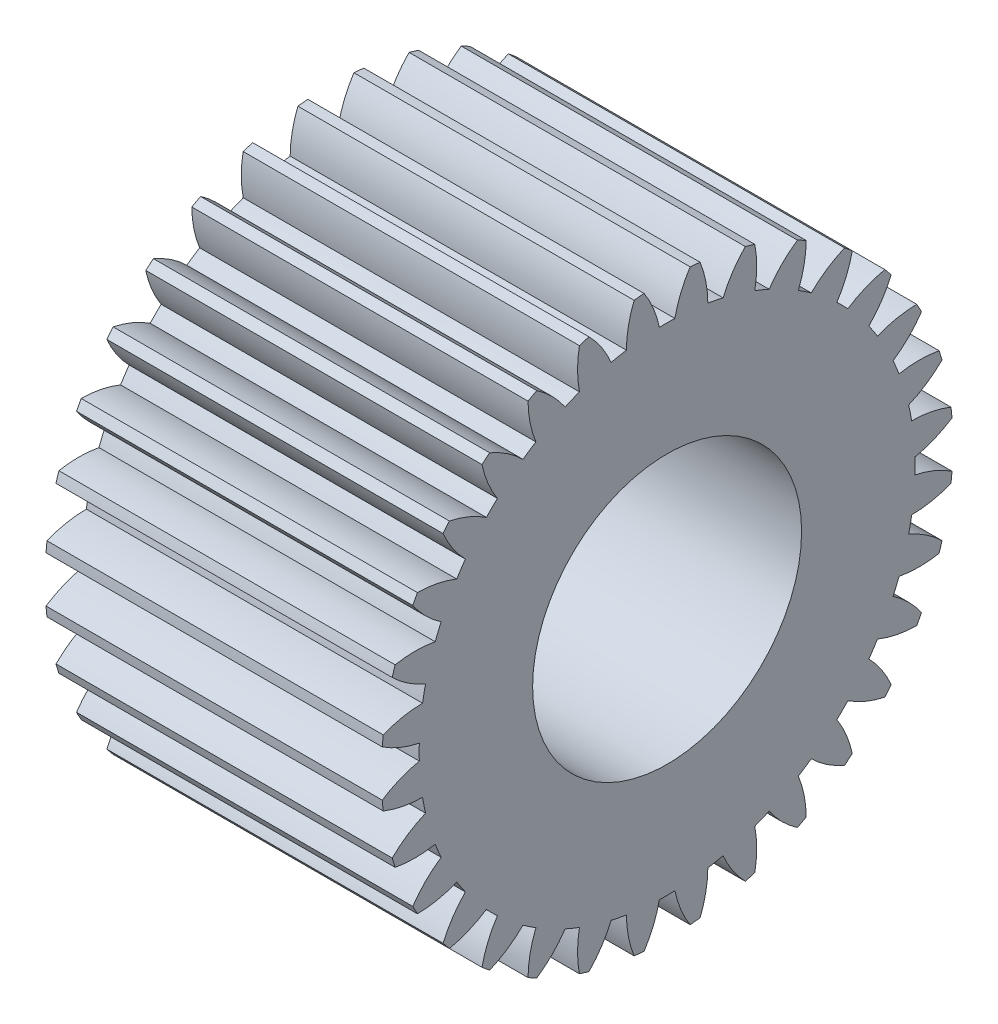
SolidWorks part; units mm, degrees
ref_plane "Plane1" through (0, 0, 0) normal (0, 0, 1) x (1, 0, 0)
ref_plane "Plane2" through (0, 0, 0) normal (0, 1, 0) x (1, 0, 0)
ref_plane "Plane3" through (0, 0, 0) normal (1, 0, 0) x (0, 0, -1)
sketch "HoldingSke" plane through (0, 0, 0) normal (0, 1, 0) x (1, 0, 0)
  line L0 (0, 0) -> (1.6961, -1.0598)
  line L1 (-15, 0) -> (100, 0) construction
  line L2 (0, 0) -> (-2.1039, 2.3779)
  line L3 (0, 0) -> (-11.863, 4.5341)
  line L4 (0, 0) -> (7.3237, 4.5764)
  line L5 (0, 0) -> (-46.8476, -17.4728)
  line L6 (0, 0) -> (-8.2896, -5.593)
  line L7 (-2.1039, 2.3779) -> (8.6586, 51.2059)
  line L8 (-76.2, 54.61) -> (-74.8, 54.61)
  line L9 (-71.009, 38.7566) -> (-53.1078, 45.2721)
  line L10 (-76.2, 71.12) -> (104.1128, 71.12)
  line L11 (0, 0) -> (-10, 0)
  line L12 (-76.2, 101.6) -> (-76.181, 101.6)
  line L13 (24.9733, 27.94) -> (52.9518, 28.4284)
  line L14 (24.9733, 27.94) -> (24.9743, 27.94)
  line L15 (24.9733, 27.94) -> (100.4006, 29.5858)
  line L16 (-63.627, -0.5) -> (-12.827, -0.5)
  circle A0 centre (0, 0) radius 4
  circle A1 centre (0, 0) radius 7.374
  circle A2 centre (0, 0) radius 37.5
  circle A3 centre (0, 0) radius 4
  dimension "MHD" = 14.748
  dimension "Hub_dia" = 75
  dimension "Bore" = 8
  dimension "MBD" = 8
  dimension "Num_teeth" = 32
  dimension "Pitch" = 2
  dimension "Overall_len" = 50
  dimension "Show_teeth" = 32
  dimension "Thickness" = 10
  dimension "OAL" = 50.0001
  dimension "T_dim" = 1.4
  dimension "Ap" = 20
  dimension "H" = 19.05
  dimension "Pitch_radius" = 180.3128
  dimension "Width" = 10
  dimension "Backlash" = 0.019
  dimension "Addendum_fac" = 1
  dimension "Dedendum_fac" = 1.25
  dimension "Clearance_fac" = 0.25
  dimension "Dedendum_add" = 0.001
  dimension "Module" = 0.5
sketch "BasProSke" plane through (0, 0, 0) normal (0, 1, 0) x (1, 0, 0)
  line L0 (-10, 0) -> (60, 0) construction
  line L1 (0, 0) -> (0, 8.5)
  line L2 (0, 0) -> (10, 0)
  line L3 (10, 0) -> (10, 8.5)
  line L4 (10, 8.5) -> (0, 8.5)
  dimension "Thickness" = 10
  dimension "Diameter" = 17
revolve "Base-Revolve" add sketch "BasProSke" angle 360 about L0
sketch "TooCutSke" plane through (0, 0, 0) normal (1, 0, 0) x (0, 0, -1)
  line L1 (0, 0) -> (0, 107) construction
  line L2 (0, 0) -> (-0.4258, 7.9887) construction
  line L3 (0, 0) -> (-1.5667, 15.9069) construction
  line L4 (-0.4258, 7.9887) -> (-0.7833, 7.9534) construction
  arc A0 (0.2309, 7.3704) -> (-0.2309, 7.3704) centre (0, 0) ccw
  arc A1 (0.7014, 8.4965) -> (-0.7014, 8.4965) centre (0, 0) ccw
  circle A2 centre (0, 0) radius 8 construction
  circle A3 centre (0, 0) radius 7.5175 construction
  arc A4 (-0.2309, 7.3704) -> (-0.7014, 8.4965) centre (-3.3647, 6.7225) ccw
  arc A5 (0.7014, 8.4965) -> (0.2309, 7.3704) centre (3.3647, 6.7225) ccw
  dimension "Root_dia" = 14.748
  dimension "Overcut_dia" = 17.0508
  dimension "Pitch_dia" = 16
  dimension "Base_dia" = 15.0351
  dimension "Flank_rad" = 3.2
  dimension "Half_ang" = 5.625
  dimension "Half_CT" = 0.3593
extrude "ToothCut" cut sketch "TooCutSke" along normal through all
fillet "Breaks" [suppressed] radius 0.01
fillet "RootFillets" [suppressed] radius 0.126
pattern_circular "TeethCuts" count 32 every 11.25 about axis through (-10, 0, 0) along (1, 0, 0) of "ToothCut", "RootFillets", "Breaks"
sketch "HubNeaOneSke" plane through (0, 0, 0) normal (-1, 0, 0) x (0, 0, 1)
  circle A0 centre (0, 0) radius 7.374
  dimension "Diameter" = 14.748
extrude "HubNearOne" [suppressed] add sketch "HubNeaOneSke" along normal blind 40.0001
sketch "HubNeaBotSke" plane through (0, 0, 0) normal (-1, 0, 0) x (0, 0, 1)
  circle A0 centre (0, 0) radius 7.374
  dimension "Diameter" = 14.748
extrude "HubNearBoth" [suppressed] add sketch "HubNeaBotSke" along normal blind 20
ref_plane "FarPln" through (10, 0, 0) normal (1, 0, 0) x (0, 0, -1)
sketch "HubFarSke" plane through (10, 0, 0) normal (1, 0, 0) x (0, 0, -1)
  circle A0 centre (0, 0) radius 7.374
  dimension "Diameter" = 14.748
extrude "HubFar" [suppressed] add sketch "HubFarSke" along normal blind 20
sketch "BorSke" plane through (0, 0, 0) normal (1, 0, 0) x (0, 0, -1)
  circle A0 centre (0, 0) radius 4
  dimension "Diameter" = 8
extrude "Bore" cut sketch "BorSke" along normal mid plane 100.0001
sketch "KeySke" plane through (0, 0, 0) normal (1, 0, 0) x (0, 0, -1)
  line L0 (-1.5, 0) -> (-1.5, 5.4)
  line L1 (-1.5, 5.4) -> (1.5, 5.4)
  line L2 (1.5, 5.4) -> (1.5, 0)
  line L3 (0, 0) -> (0, 34) construction
  line L4 (-1.5, 0) -> (1.5, 0)
  dimension "Offset" = 5.4
  dimension "Width" = 3
extrude "Keyway" [suppressed] cut sketch "KeySke" along normal mid plane 100.0001
pattern_circular "Keyway2" [suppressed] count 2 every 90 about axis through (-10, 0, 0) along (1, 0, 0)
equation "' \"Module@HoldingSke\" = 6.35"
equation "' \"Num_teeth@HoldingSke\" = 12"
equation "' \"Ap@HoldingSke\" =  20"
equation "' \"Ap@HoldingSke\" = 20"
equation "' \"Width@HoldingSke\" = 0.5 * 25.4"
equation "' \"Hub_dia@HoldingSke\"= 1 * 25.4"
equation "' \"Hub_dia@HoldingSke\" = 1 * 25.4"
equation "' \"Overall_len@HoldingSke\" = 1.0 * 25.4"
equation "' \"Bore@HoldingSke\" = 0.75 * 25.4"
equation "' \"T_dim@HoldingSke\" = 0.1 * 25.4"
equation "' \"Width@KeySke\" = 0.25 * 25.4"
equation "' \"Show_teeth@HoldingSke\" = 13"
equation "' \"Backlash@HoldingSke\" = 0.009 * 25.4"
equation "' \"Addendum_fac@HoldingSke\" = 1.0"
equation "' \"Dedendum_fac@HoldingSke\" = 1.25"
equation "' \"Dedendum_add@HoldingSke\" = 0.00005 * 25.4"
equation "' \"Clearance_fac@HoldingSke\" = 0.25"
equation "\"Pitch@HoldingSke\" = 1 / \"Module@HoldingSke\""
equation "\"Overcut_dia@TooCutSke\" = (\"Num_teeth@HoldingSke\" + 2 * \"Addendum_fac@HoldingSke\") / \"Pitch@HoldingSke\" + 0.002 * 25.4"
equation "\"Pitch_dia@TooCutSke\" = \"Num_teeth@HoldingSke\" / \"Pitch@HoldingSke\""
equation "\"Base_dia@TooCutSke\" = \"Num_teeth@HoldingSke\" / \"Pitch@HoldingSke\" * cos((\"Ap@HoldingSke\"  * 3.14159265 / 180))"
equation "\"Root_dia@TooCutSke\" = (\"Num_teeth@HoldingSke\" + 2) / \"Pitch@HoldingSke\" - 2 * (\"Addendum_fac@HoldingSke\" + \"Dedendum_fac@HoldingSke\") / \"Pitch@HoldingSke\" - \"Dedendum_add@HoldingSke\" * 2"
equation "\"Half_ang@TooCutSke\" = 180 / \"Num_teeth@HoldingSke\""
equation "\"Half_CT@TooCutSke\" = \"Num_teeth@HoldingSke\" / \"Pitch@HoldingSke\" * sin((3.14159265 / 2 / \"Num_teeth@HoldingSke\")) / 2 - 7 * \"Backlash@HoldingSke\" / 4"
equation "\"Flank_rad@TooCutSke\" = \"Num_teeth@HoldingSke\" / \"Pitch@HoldingSke\" / 5"
equation "\"Radius@RootFillets\" = \"Clearance_fac@HoldingSke\" / \"Pitch@HoldingSke\" + \"Dedendum_add@HoldingSke\""
equation "\"Break_rad@Breaks\" = 0.02 / \"Pitch@HoldingSke\""
equation "\"Thickness@HoldingSke\" = \"Width@HoldingSke\""
equation "\"OAL@HoldingSke\" = \"Thickness@HoldingSke\""
equation "\"MHD@HoldingSke\" = (\"Num_teeth@HoldingSke\" + 2) / \"Pitch@HoldingSke\" - 2 * (\"Addendum_fac@HoldingSke\" + \"Dedendum_fac@HoldingSke\")  / \"Pitch@HoldingSke\" - \"Dedendum_add@HoldingSke\" * 2"
equation "\"MBD@HoldingSke\" = (\"Num_teeth@HoldingSke\" + 2) / \"Pitch@HoldingSke\" - 2 * (\"Addendum_fac@HoldingSke\" + \"Dedendum_fac@HoldingSke\")  / \"Pitch@HoldingSke\" - \"Dedendum_add@HoldingSke\" * 2 - 0.002 * 25.4"
equation "\"MHD@HoldingSke\" = ((sgn( \"MHD@HoldingSke\" - \"Hub_dia@HoldingSke\" )-1)*( \"MHD@HoldingSke\" - \"Hub_dia@HoldingSke\" ))/-2+ \"Hub_dia@HoldingSke\""
equation "\"MBD@HoldingSke\" = ((sgn( \"MBD@HoldingSke\" - \"Bore@HoldingSke\" )-1)*( \"MBD@HoldingSke\" - \"Bore@HoldingSke\" ))/-2+ \"Bore@HoldingSke\""
equation "\"OAL@HoldingSke\" = ((sgn( \"OAL@HoldingSke\" - \"Overall_len@HoldingSke\" )+1)*( \"OAL@HoldingSke\" - \"Overall_len@HoldingSke\" ))/2 + \"Overall_len@HoldingSke\" + 0.000002 * 25.4"
equation "\"Num_teeth@TeethCuts\" = int( \"Show_teeth@HoldingSke\" ) + 1"
equation "\"Num_teeth@TeethCuts\" = ((sgn( \"Num_teeth@TeethCuts\" - \"Num_teeth@HoldingSke\" )-1)*( \"Num_teeth@TeethCuts\" - \"Num_teeth@HoldingSke\" ))/-2+ \"Num_teeth@HoldingSke\""
equation "\"Num_teeth@TeethCuts\" = ((sgn( \"Num_teeth@TeethCuts\" - 2.0)+1)*( \"Num_teeth@TeethCuts\" - 2.0))/2 +2.0"
equation "\"Angle@TeethCuts\" = 360.0 / \"Num_teeth@HoldingSke\""
equation "\"Diameter@BasProSke\" = (\"Num_teeth@HoldingSke\" + 2 * \"Addendum_fac@HoldingSke\") / \"Pitch@HoldingSke\""
equation "\"Thickness@BasProSke\"  = \"Thickness@HoldingSke\""
equation "' \"Fillet_rad@BasProSke\" =  \"Thickness@HoldingSke\" * 0.05"
equation "' \"Fillet_rad@BasProSke\" = \"Thickness@HoldingSke\" * 0.05"
equation "\"MHD@HoldingSke\" = ((sgn( \"MHD@HoldingSke\" - \"Root_dia@TooCutSke\" )-1)*( \"MHD@HoldingSke\" - \"Root_dia@TooCutSke\" ))/-2+ \"Root_dia@TooCutSke\""
equation "\"Diameter@HubNeaOneSke\" = \"MHD@HoldingSke\""
equation "\"Length@HubNearOne\" = \"OAL@HoldingSke\" - \"Thickness@BasProSke\""
equation "\"Diameter@HubNeaBotSke\" = \"MHD@HoldingSke\""
equation "\"Length@HubNearBoth\" = ( \"OAL@HoldingSke\" - \"Thickness@BasProSke\" ) / 2.0"
equation "\"Thickness@FarPln\" = \"Thickness@BasProSke\""
equation "\"Diameter@HubFarSke\" = \"MHD@HoldingSke\""
equation "\"Length@HubFar\" = ( \"OAL@HoldingSke\" - \"Thickness@BasProSke\" ) / 2.0"
equation "\"Diameter@BorSke\" = \"MBD@HoldingSke\""
equation "\"D1@Bore\" = \"OAL@HoldingSke\" * 2.0"
equation "\"D1@Keyway\" = \"OAL@HoldingSke\" * 2.0"
equation "\"Offset@KeySke\" = \"T_dim@HoldingSke\" + \"MBD@HoldingSke\" / 2.0"
